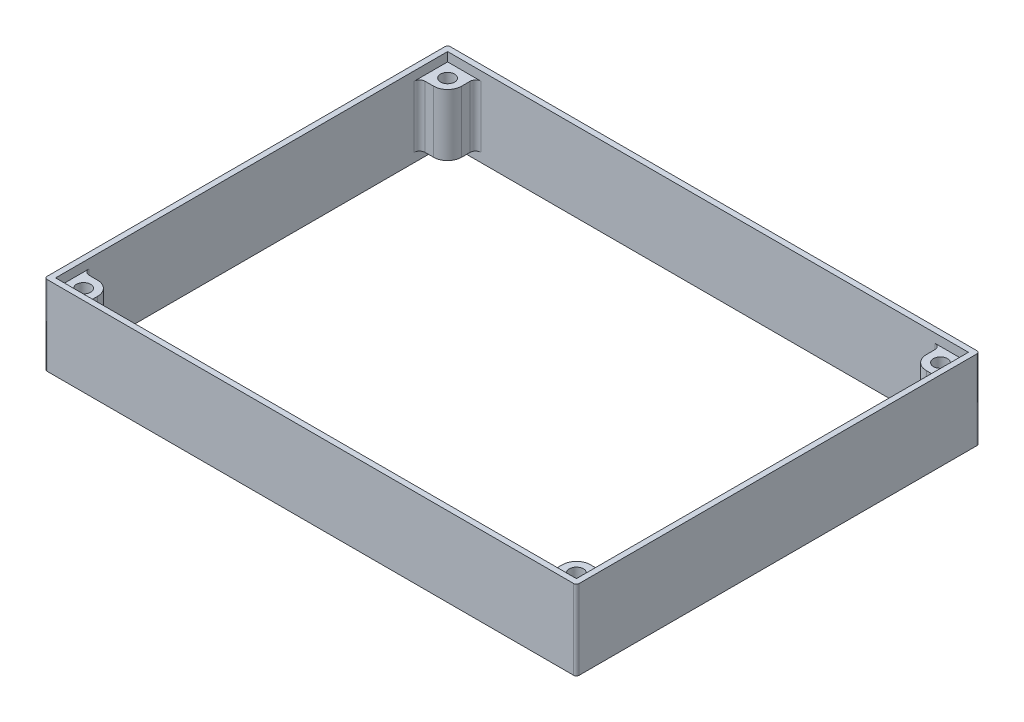
SolidWorks part; units mm, degrees
ref_plane "Front" through (0, 0, 0) normal (0, 0, 1) x (1, 0, 0)
ref_plane "Top" through (0, 0, 0) normal (0, 1, 0) x (1, 0, 0)
ref_plane "Right" through (0, 0, 0) normal (1, 0, 0) x (0, 0, -1)
sketch "Sketch1" plane through (0, 0, 0) normal (0, 1, 0) x (1, 0, 0)
  line L0 (0, 0) -> (0, 49.6813) construction
  line L1 (0, 0) -> (-53.3518, 0) construction
  line L2 (-44, 30) -> (-46.5, 30)
  line L3 (-46.5, 30) -> (-46.5, -30)
  line L4 (-41.5, 32.5) -> (-41.5, 35)
  line L5 (-41.5, 35) -> (41.5, 35)
  line L6 (-47.5, -36) -> (-47.5, 36)
  line L7 (-47.5, 36) -> (47.5, 36)
  line L8 (47.5, -36) -> (47.5, 36)
  line L9 (41.5, 32.5) -> (41.5, 35)
  line L10 (46.5, 30) -> (46.5, -30)
  line L11 (44, 30) -> (46.5, 30)
  line L12 (44, -30) -> (46.5, -30)
  line L13 (41.5, -32.5) -> (41.5, -35)
  line L14 (-47.5, -36) -> (47.5, -36)
  line L15 (-41.5, -35) -> (41.5, -35)
  line L16 (-41.5, -32.5) -> (-41.5, -35)
  line L17 (-44, -30) -> (-46.5, -30)
  circle A0 centre (-44, 32.5) radius 2.5 construction
  arc A1 (-41.5, 32.5) -> (-44, 30) centre (-44, 32.5) cw
  circle A2 centre (-44, 32.5) radius 1.25
  circle A3 centre (44, 32.5) radius 2.5 construction
  circle A4 centre (44, 32.5) radius 1.25
  arc A5 (41.5, 32.5) -> (44, 30) centre (44, 32.5) ccw
  circle A6 centre (44, -32.5) radius 2.5 construction
  circle A7 centre (-44, -32.5) radius 2.5 construction
  arc A8 (41.5, -32.5) -> (44, -30) centre (44, -32.5) cw
  circle A9 centre (44, -32.5) radius 1.25
  circle A10 centre (-44, -32.5) radius 1.25
  arc A11 (-41.5, -32.5) -> (-44, -30) centre (-44, -32.5) ccw
  point P0 (-44, 32.5)
  point P10 (0, -35)
  point P24 (0, 36)
  point P26 (0, 35)
  point P39 (46.5, 0)
  point P41 (47.5, 0)
  point P42 (-47.5, 0)
  point P44 (-46.5, 0)
  point P45 (0, -36)
  dimension "D3" = 5
  dimension "D6" = 2.5
  dimension "D1" = 44
  dimension "D2" = 32.5
  dimension "D4" = 1
  dimension "D5" = 1
extrude "Boss-Extrude1" add sketch "Sketch1" along normal blind 14.2
fillet "Fillet1" radius 0.5 4 edges at (-47.5, 7.1, -36) (47.5, 7.1, -36) (47.5, 7.1, 36) (-47.5, 7.1, 36)
fillet "Fillet2" radius 1 8 edges at (-46.5, 7.1, 30) (-41.5, 7.1, 35) (46.5, 7.1, 30) (41.5, 7.1, 35) (41.5, 7.1, -35) (46.5, 7.1, -30) (-46.5, 7.1, -30) (-41.5, 7.1, -35)
sketch "Sketch2" plane through (0, 14.2, 0) normal (0, 1, 0) x (1, 0, 0)
  line L1 (-46.5, -35) -> (46.5, -35)
  line L2 (-46.5, -35) -> (-46.5, 35)
  line L3 (-46.5, 35) -> (46.5, 35)
  line L4 (46.5, -35) -> (46.5, 35)
  line L5 (-46.5, -35) -> (46.5, 35) construction
  line L6 (-46.5, 35) -> (46.5, -35) construction
  point P0 (0, 0)
  dimension "D1" = 93
  dimension "D2" = 70
extrude "Cut-Extrude1" cut sketch "Sketch2" against normal blind 1.6
sketch "Sketch3" plane through (0, 0, 0) normal (0, -1, 0) x (1, 0, 0)
  line L1 (46.5, -35) -> (-46.5, -35)
  line L2 (46.5, -35) -> (46.5, 35)
  line L3 (46.5, 35) -> (-46.5, 35)
  line L4 (-46.5, -35) -> (-46.5, 35)
  line L5 (46.5, -35) -> (-46.5, 35) construction
  line L6 (46.5, 35) -> (-46.5, -35) construction
  point P0 (0, 0)
  dimension "D1" = 93
  dimension "D2" = 70
extrude "Cut-Extrude2" cut sketch "Sketch3" against normal blind 1.6
